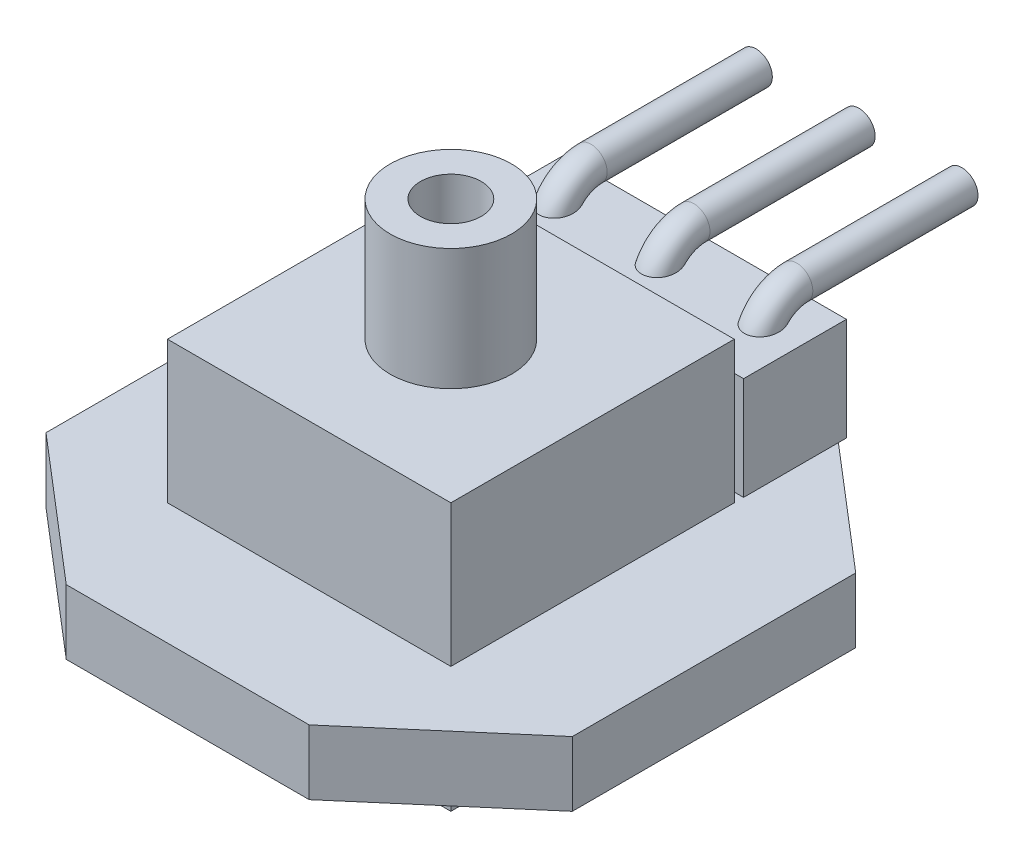
SolidWorks part; units mm, degrees
ref_plane "Front" through (0, 0, 0) normal (0, 0, 1) x (1, 0, 0)
ref_plane "Top" through (0, 0, 0) normal (0, 1, 0) x (1, 0, 0)
ref_plane "Right" through (0, 0, 0) normal (1, 0, 0) x (0, 0, -1)
sketch "Эскиз1" plane through (0, 0, 0) normal (0, 1, 0) x (1, 0, 0)
  line L0 (-3, 6.5) -> (3, 6.5)
  line L1 (3, 6.5) -> (6.5, 3.5)
  line L2 (6.5, 3.5) -> (6.5, -3.5)
  line L3 (6.5, -3.5) -> (3, -6.5)
  line L4 (3, -6.5) -> (-3, -6.5)
  line L5 (-3, -6.5) -> (-6.5, -3.5)
  line L6 (-6.5, -3.5) -> (-6.5, 3.5)
  line L7 (-6.5, 3.5) -> (-3, 6.5)
  point P8 (0, 6.5)
  point P10 (0, -6.5)
  point P11 (-6.5, 0)
  point P12 (6.5, 0)
  dimension "D1" = 13
  dimension "D2" = 13
  dimension "D3" = 7
  dimension "D4" = 6
extrude "База" add sketch "Эскиз1" along normal blind 1.6
sketch "Эскиз2" plane through (0, 1.6, 0) normal (0, 1, 0) x (1, 0, 0)
  line L1 (-3.5, 3.5) -> (3.5, 3.5)
  line L2 (-3.5, 3.5) -> (-3.5, -3.5)
  line L3 (-3.5, -3.5) -> (3.5, -3.5)
  line L4 (3.5, 3.5) -> (3.5, -3.5)
  line L5 (-3.5, 3.5) -> (3.5, -3.5) construction
  line L6 (-3.5, -3.5) -> (3.5, 3.5) construction
  point P0 (0, 0)
  dimension "D1" = 7
  dimension "D2" = 7
extrude "Бобышка-Вытянуть2" add sketch "Эскиз2" along normal blind 3.5
sketch "Эскиз3" plane through (0, 5.1, 0) normal (0, 1, 0) x (1, 0, 0)
  circle A0 centre (0, 0) radius 0.75
  circle A1 centre (0, 0) radius 1.5
  dimension "D1" = 1.5
  dimension "D2" = 3
extrude "Бобышка-Вытянуть3" add sketch "Эскиз3" along normal blind 3
sketch "Эскиз6" plane through (0, 0, 0) normal (0, -1, 0) x (1, 0, 0)
  line L1 (-3, 3) -> (3, 3)
  line L2 (-3, 3) -> (-3, -3)
  line L3 (-3, -3) -> (3, -3)
  line L4 (3, 3) -> (3, -3)
  line L5 (-3, 3) -> (3, -3) construction
  line L6 (-3, -3) -> (3, 3) construction
  point P0 (0, 0)
  dimension "D1" = 6
  dimension "D2" = 6
extrude "Бобышка-Вытянуть6" add sketch "Эскиз6" along normal blind 2
sketch "Эскиз7" plane through (0, 0, 0) normal (1, 0, 0) x (0, 0, -1)
  line L0 (5, 1.6) -> (5, 3.6)
  line L1 (3.5, 1.6) -> (6.5, 1.6) construction
  line L2 (6, 4.6) -> (10.08, 4.6)
  arc A0 (5, 3.6) -> (6, 4.6) centre (6, 3.6) cw
  point P8 (5, 4.6)
  dimension "D4" = 1
  dimension "D1" = 3
  dimension "D2" = 5.08
  dimension "D3" = 5
sketch "Эскиз4" plane through (0, 1.6, 0) normal (0, -1, 0) x (1, 0, 0)
  line L0 (0, -6) -> (0, -10.08) construction
  circle A6 centre (0, -5) radius 0.4
  dimension "D2" = 5
  dimension "D1" = 0.8
sweep "По траектории1" add profiles "Эскиз4" path "Эскиз7"
pattern_linear "Линейный массив1" count 2 spacing 2.54 along (1, 0, 0) count 2 spacing 2.54 along (-1, 0, 0) of "По траектории1"
sketch "Эскиз8" plane through (0, 1.6, 0) normal (0, 1, 0) x (1, 0, 0)
  line L1 (-3.5, 3.73) -> (3.5, 3.73)
  line L2 (-3.5, 3.73) -> (-3.5, 6.27)
  line L3 (-3.5, 6.27) -> (3.5, 6.27)
  line L4 (3.5, 3.73) -> (3.5, 6.27)
  line L5 (-3.5, 3.73) -> (3.5, 6.27) construction
  line L6 (-3.5, 6.27) -> (3.5, 3.73) construction
  point P0 (0, 5)
  dimension "D1" = 2.54
  dimension "D2" = 7
extrude "Бобышка-Вытянуть7" add sketch "Эскиз8" along normal blind 2.54
